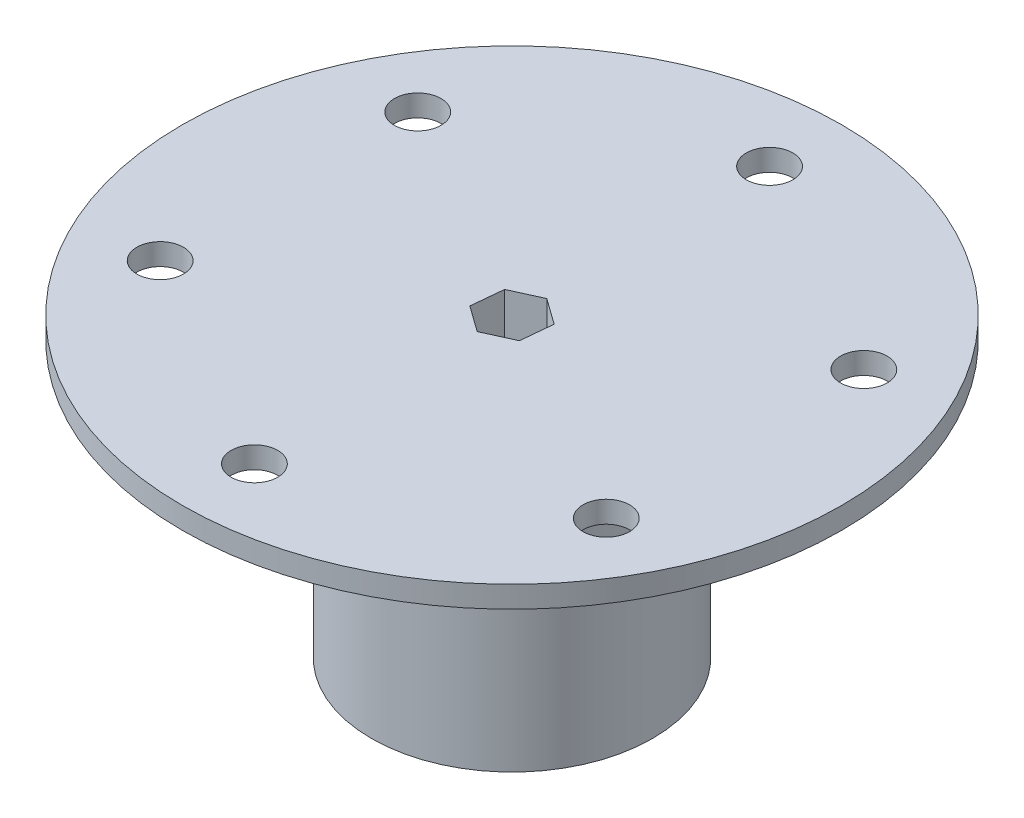
SolidWorks part; units mm, degrees
ref_plane "Front" through (0, 0, 0) normal (0, 0, 1) x (1, 0, 0)
ref_plane "Top" through (0, 0, 0) normal (0, 1, 0) x (1, 0, 0)
ref_plane "Right" through (0, 0, 0) normal (1, 0, 0) x (0, 0, -1)
sketch "Sketch1" plane through (0, 0, 0) normal (0, 1, 0) x (1, 0, 0)
  circle A1 centre (0, 0) radius 30.48
  circle A2 centre (0, -23.8125) radius 2.1526
  circle A3 centre (20.6222, -11.9062) radius 2.1526
  circle A4 centre (20.6222, 11.9063) radius 2.1526
  circle A5 centre (0, 23.8125) radius 2.1526
  circle A6 centre (-20.6222, 11.9062) radius 2.1527
  circle A7 centre (-20.6222, -11.9062) radius 2.1527
extrude "Boss-Extrude1" add sketch "Sketch1" along normal blind 2
sketch "Sketch2" plane through (0, 2, 0) normal (0, 1, 0) x (1, 0, 0)
  line L1 (-2.6806, -1.2183) -> (-0.2852, -2.9306)
  line L2 (-0.2852, -2.9306) -> (2.3954, -1.7123)
  line L3 (2.3954, -1.7123) -> (2.6806, 1.2183)
  line L4 (2.6806, 1.2183) -> (0.2852, 2.9306)
  line L5 (0.2852, 2.9306) -> (-2.3954, 1.7123)
  line L6 (-2.3954, 1.7123) -> (-2.6806, -1.2183)
  circle A1 centre (0, 0) radius 2.55 construction
  dimension "D1" = 5.1
extrude "Cut-Extrude1" cut sketch "Sketch2" against normal blind 10
sketch "Sketch3" plane through (0, 0, 0) normal (0, -1, 0) x (1, 0, 0)
  line L1 (-0.2852, 2.9306) -> (-2.6806, 1.2183)
  line L2 (-2.6806, 1.2183) -> (-2.3954, -1.7123)
  line L3 (-2.3954, -1.7123) -> (0.2852, -2.9306)
  line L4 (0.2852, -2.9306) -> (2.6806, -1.2183)
  line L5 (2.6806, -1.2183) -> (2.3954, 1.7123)
  line L6 (2.3954, 1.7123) -> (-0.2852, 2.9306)
  circle A0 centre (0, 0) radius 13
  circle A2 centre (0, 0) radius 2.55 construction
  dimension "D1" = 26
extrude "Boss-Extrude2" add sketch "Sketch3" along normal blind 25.4
